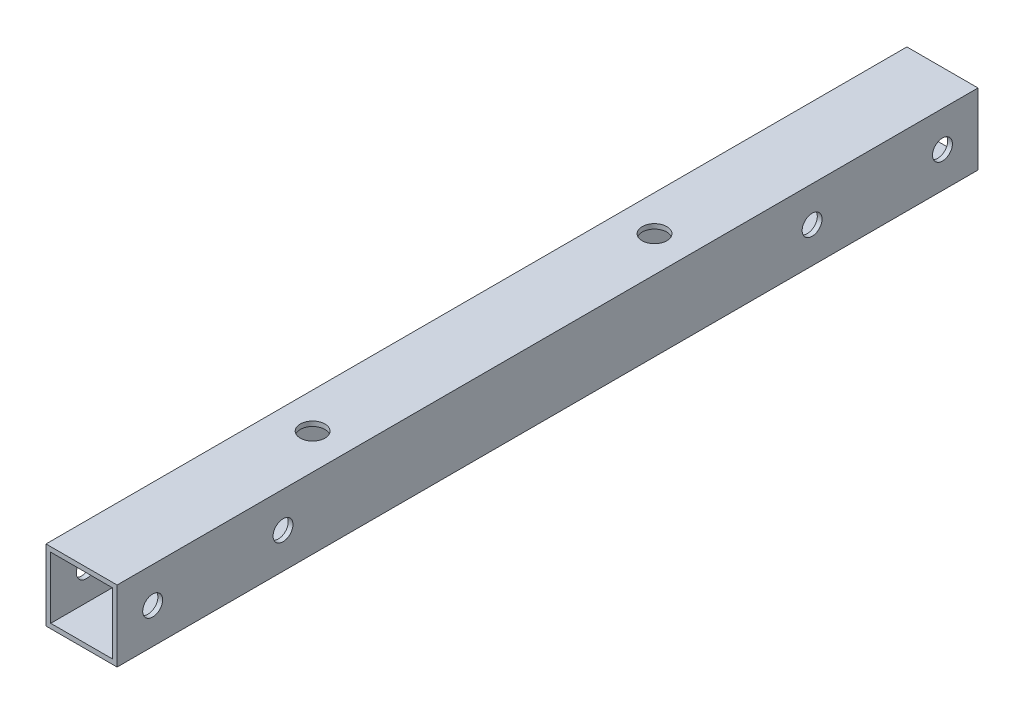
SolidWorks part; units mm, degrees
material "1060 合金"
ref_plane "正面" through (0, 0, 0) normal (0, 0, 1) x (1, 0, 0)
ref_plane "平面" through (0, 0, 0) normal (0, 1, 0) x (1, 0, 0)
ref_plane "右側面" through (0, 0, 0) normal (1, 0, 0) x (0, 0, -1)
sketch "ｽｹｯﾁ1" plane through (0, 0, 0) normal (0, 0, 1) x (1, 0, 0)
  line L1 (7.5, 7.5) -> (-7.5, 7.5)
  line L2 (7.5, 7.5) -> (7.5, -7.5)
  line L3 (7.5, -7.5) -> (-7.5, -7.5)
  line L4 (-7.5, 7.5) -> (-7.5, -7.5)
  line L5 (7.5, 7.5) -> (-7.5, -7.5) construction
  line L6 (7.5, -7.5) -> (-7.5, 7.5) construction
  point P0 (0, 0)
  dimension "D1" = 15
extrude "押し出し-薄板1" add sketch "ｽｹｯﾁ1" along normal blind 181.6 thin thin type one direction reverse wall 1
sketch "ｽｹｯﾁ2" plane through (0, 7.5, 0) normal (0, 1, 0) x (1, 0, 0)
  line L0 (0, 0) -> (0, -181.6) construction
  line L1 (7.5, -181.6) -> (-7.5, -181.6) construction
  circle A0 centre (0, -132.86) radius 2.6
  circle A1 centre (0, -60.74) radius 2.6
  point P7 (0, -42.74)
  dimension "D1" = 72.12
  dimension "D2" = 5.2
  dimension "D3" = 48.74
extrude "ｶｯﾄ - 押し出し1" cut sketch "ｽｹｯﾁ2" against normal through all
sketch "ｽｹｯﾁ3" plane through (-7.5, 0, 0) normal (-1, 0, 0) x (0, 0, 1)
  line L0 (0, 0) -> (181.6, 0) construction
  line L1 (181.6, 7.5) -> (181.6, -7.5) construction
  line L2 (90.8, 0) -> (90.8, 7.5) construction
  line L3 (181.6, 7.5) -> (0, 7.5) construction
  circle A0 centre (174.1, 0) radius 2.1
  circle A1 centre (146.6, 0) radius 2.1
  circle A4 centre (35, 0) radius 2.1
  circle A5 centre (7.5, 0) radius 2.1
  dimension "D1" = 7.5
  dimension "D2" = 27.5
  dimension "D4" = 4.2
extrude "ｶｯﾄ - 押し出し2" cut sketch "ｽｹｯﾁ3" against normal through all
